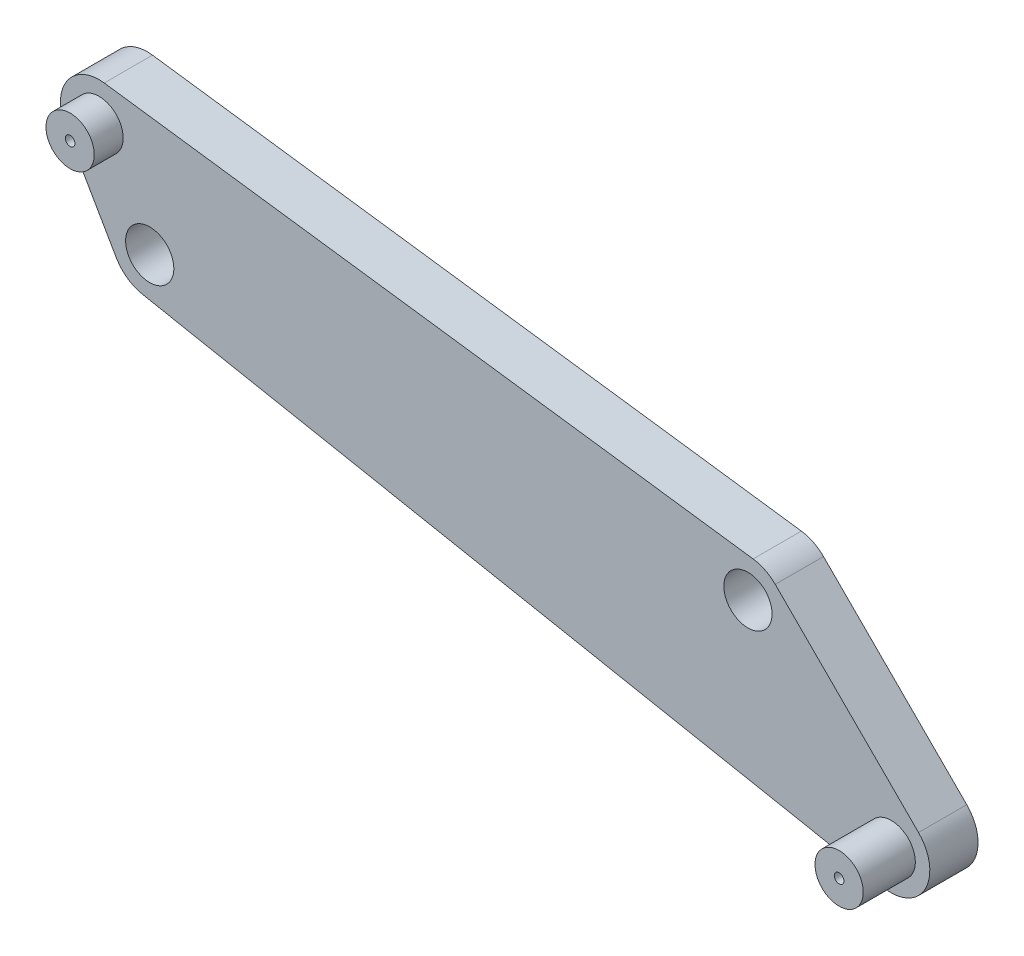
SolidWorks part; units mm, degrees
material "ABS"
ref_plane "Front Plane" through (0, 0, 0) normal (0, 0, 1) x (1, 0, 0)
ref_plane "Top Plane" through (0, 0, 0) normal (0, 1, 0) x (1, 0, 0)
ref_plane "Right Plane" through (0, 0, 0) normal (1, 0, 0) x (0, 0, -1)
sketch "Sketch1" plane through (0, 0, 0) normal (0, 0, 1) x (1, 0, 0)
  line L0 (0, 0) -> (-62, 0)
  line L1 (-62, 0) -> (-67.25, 9.0933)
  line L2 (0, 0) -> (14.8492, -14.8492)
  dimension "D1" = 62
  dimension "D2" = 10.5
  dimension "D3" = 21
  dimension "D4" = 120
  dimension "D5" = 135
sketch "Sketch2" plane through (0, 0, 0) normal (0, 0, 1) x (1, 0, 0)
  line L0 (-66.714, 13.0572) -> (0.536, 3.9639)
  line L1 (2.8284, 2.8284) -> (17.6777, -12.0208)
  line L2 (14.0904, -18.7766) -> (-62.7589, -3.9274)
  line L3 (-65.4641, -2) -> (-70.7141, 7.0933)
  circle A0 centre (-62, 0) radius 2.5
  circle A1 centre (-67.25, 9.0933) radius 2.5
  arc A2 (-66.714, 13.0572) -> (-70.7141, 7.0933) centre (-67.25, 9.0933) ccw
  arc A3 (-65.4641, -2) -> (-62.7589, -3.9274) centre (-62, 0) ccw
  circle A4 centre (0, 0) radius 2.5
  circle A5 centre (14.8492, -14.8492) radius 2.5
  arc A6 (2.8284, 2.8284) -> (0.536, 3.9639) centre (0, 0) ccw
  arc A7 (14.0904, -18.7766) -> (17.6777, -12.0208) centre (14.8492, -14.8492) ccw
  dimension "D1" = 5
  dimension "D2" = 5
  dimension "D3" = 5
  dimension "D4" = 5
  dimension "D5" = 8
  dimension "D6" = 8
  dimension "D7" = 8
  dimension "D8" = 8
extrude "Boss-Extrude1" add sketch "Sketch2" along normal blind 5
sketch "Sketch4" plane through (0, 0, 0) normal (0, 0, -1) x (-1, 0, 0)
  circle A0 centre (67.25, 9.0933) radius 2.5
  circle A1 centre (67.25, 9.0933) radius 0.5
  circle A2 centre (-14.8492, -14.8492) radius 2.5
  circle A3 centre (-14.8492, -14.8492) radius 0.5
  dimension "D1" = 1
  dimension "D2" = 5
  dimension "D3" = 5
  dimension "D4" = 1
extrude "Boss-Extrude3" add sketch "Sketch4" against normal blind 8
sketch "Sketch5" plane through (0, 0, 8) normal (0, 0, 1) x (1, 0, 0)
  circle A0 centre (14.8492, -14.8492) radius 2.5
  circle A1 centre (14.8492, -14.8492) radius 0.5
  dimension "D1" = 5
  dimension "D2" = 1
extrude "Boss-Extrude4" add sketch "Sketch5" along normal blind 2.4
